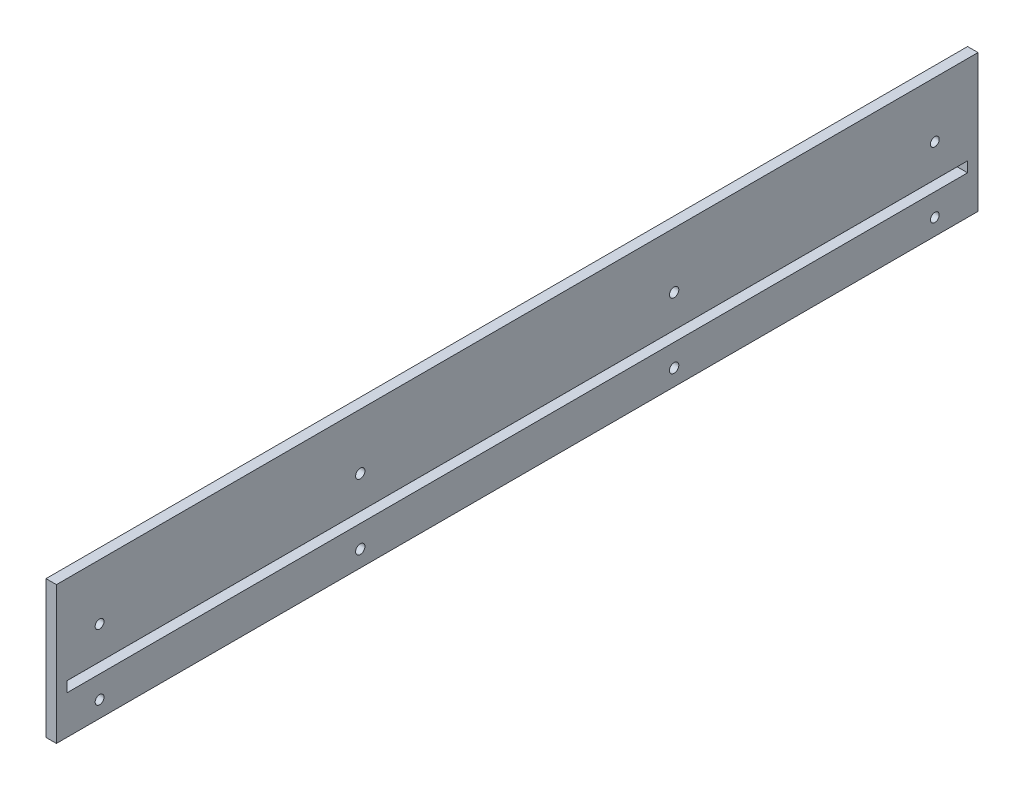
SolidWorks part; units mm, degrees
ref_plane "Front Plane" through (0, 0, 0) normal (0, 0, 1) x (1, 0, 0)
ref_plane "Top Plane" through (0, 0, 0) normal (0, 1, 0) x (1, 0, 0)
ref_plane "Right Plane" through (0, 0, 0) normal (1, 0, 0) x (0, 0, -1)
sketch "Sketch1" plane through (0, 0, 0) normal (1, 0, 0) x (0, 0, -1)
  line L1 (-140.68, 15) -> (140.68, 15)
  line L2 (-140.68, 15) -> (-140.68, -15)
  line L3 (-140.68, -15) -> (140.68, -15)
  line L4 (140.68, 15) -> (140.68, -15)
  line L5 (-140.68, 15) -> (140.68, -15) construction
  line L6 (-140.68, -15) -> (140.68, 15) construction
  point P0 (0, 0)
  dimension "D1" = 30
  dimension "D2" = 281.36
extrude "Boss-Extrude1" add sketch "Sketch1" along normal blind 3.18
sketch "Sketch2" plane through (0, 0, 0) normal (-1, 0, 0) x (0, 0, 1)
  line L0 (-140.68, 0) -> (0, 0) construction
  line L1 (-140.68, -15) -> (-140.68, 15) construction
  line L2 (0, 0) -> (0, 15) construction
  line L3 (-140.68, 15) -> (140.68, 15) construction
  line L4 (0, 7.5) -> (-140.68, 7.5) construction
  line L5 (-127.5, 10) -> (-127.5, 5) construction
  line L6 (-127.5, 10) -> (-47.91, 10) construction
  circle A0 centre (-127.5, 10) radius 1.35
  circle A1 centre (-47.91, 10) radius 1.425
  point P14 (-127.5, 7.5)
  dimension "D1" = 2.7
  dimension "D2" = 5
  dimension "D5" = 2.85
  dimension "D3" = 13.18
  dimension "D4" = 79.59
extrude "Cut-Extrude1" cut sketch "Sketch2" against normal up to next
mirror "Mirror1" about plane through (0, 0, 0) normal (0, 1, 0) of "Cut-Extrude1"
mirror "Mirror2" about plane through (0, 0, 0) normal (0, 0, 1) of "Mirror1", "Cut-Extrude1"
sketch "Sketch3" plane through (3.18, 0, 0) normal (1, 0, 0) x (0, 0, -1)
  line L1 (-137.5, -3.21) -> (137.5, -3.21)
  line L2 (-137.5, -3.21) -> (-137.5, -0.02)
  line L3 (-137.5, -0.02) -> (137.5, -0.02)
  line L4 (137.5, -3.21) -> (137.5, -0.02)
  line L6 (140.68, 15) -> (-140.68, 15) construction
  line L7 (-140.68, -15) -> (140.68, -15) construction
  point P6 (0, -3.21)
  point P9 (0, -15)
  dimension "D1" = 3.19
  dimension "D2" = 275
  dimension "D3" = 15.02
extrude "Cut-Extrude2" cut sketch "Sketch3" against normal blind 3.18
sketch "Sketch4" plane through (0, 15, 0) normal (0, 1, 0) x (1, 0, 0)
  line L1 (0, -140.68) -> (3.18, -140.68)
  line L2 (0, -140.68) -> (0, 140.68)
  line L3 (0, 140.68) -> (3.18, 140.68)
  line L4 (3.18, -140.68) -> (3.18, 140.68)
extrude "Boss-Extrude2" add sketch "Sketch4" along normal blind 12
